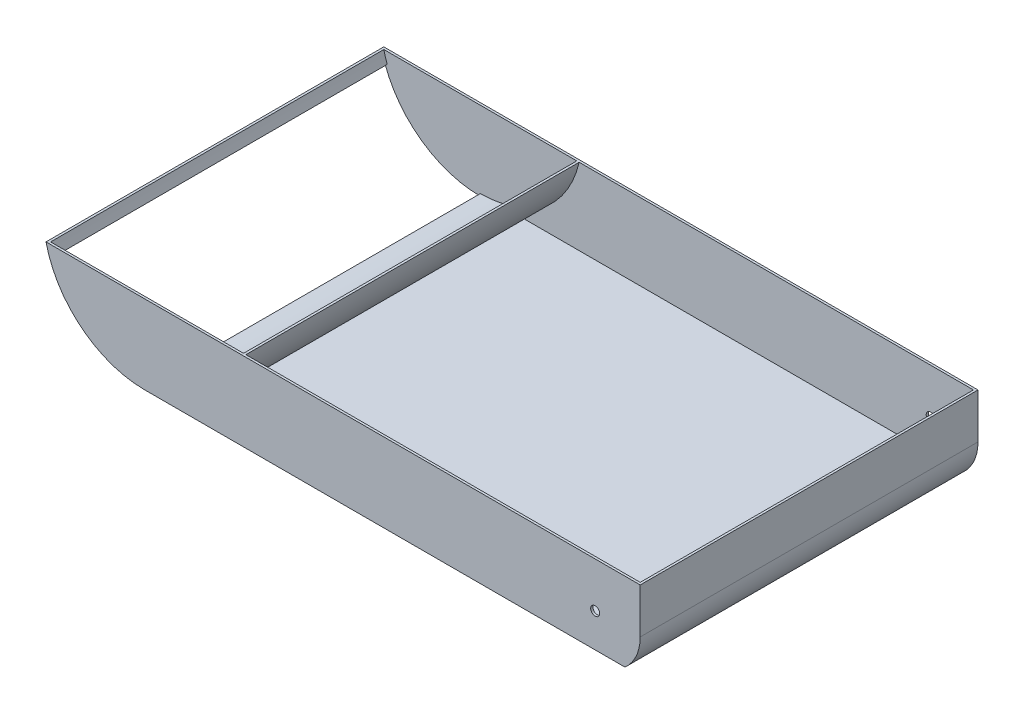
SolidWorks part; units mm, degrees
ref_plane "前视基准面" through (0, 0, 0) normal (0, 0, 1) x (1, 0, 0)
ref_plane "上视基准面" through (0, 0, 0) normal (0, 1, 0) x (1, 0, 0)
ref_plane "右视基准面" through (0, 0, 0) normal (1, 0, 0) x (0, 0, -1)
sketch "草图1" plane through (0, 0, 0) normal (0, 0, 1) x (1, 0, 0)
  line L6 (-22.8393, -20) -> (-87.7496, -20)
  line L7 (0, -90) -> (400, -90)
  line L8 (400, -90) -> (426.4575, -90)
  line L9 (-22.8393, -20) -> (400, -20)
  line L10 (440, -60) -> (440, -20)
  line L11 (440, -20) -> (400, -20)
  arc A0 (-87.7496, -20) -> (0, -90) centre (0, 0) ccw
  arc A5 (426.4575, -90) -> (440, -60) centre (400, -60) ccw
extrude "凸台-拉伸1" add sketch "草图1" against normal blind 300
shell "抽壳1" thickness 2
sketch "草图3" plane through (0, 0, -298) normal (0, 0, 1) x (1, 0, 0)
  line L0 (0, -90) -> (0, -30)
  line L1 (0, -30) -> (-101.2114, -30)
  line L2 (-101.2114, -30) -> (-101.2114, -90)
  line L3 (-101.2114, -90) -> (0, -90)
  dimension "D1" = 60
extrude "切除-拉伸1" cut sketch "草图3" along normal up to surface (296 mm away) up to face at (241.4168, -58.4456, -2)
sketch "草图4" plane through (0, 0, 0) normal (0, 0, 1) x (1, 0, 0)
  line L0 (85.6971, -20) -> (87.7496, -20)
  line L2 (0, -88) -> (0, -90)
  arc A0 (0, -90) -> (87.7496, -20) centre (0, 0) ccw
  arc A1 (0, -88) -> (85.6971, -20) centre (0, 0) ccw
extrude "凸台-拉伸2" add sketch "草图4" against normal up to surface (300 mm away) up to face at (241.9373, -59.3627, -300)
sketch "草图6" plane through (0, 0, 0) normal (0, 0, 1) x (1, 0, 0)
  circle A0 centre (400, -60) radius 4
extrude "切除-拉伸2" cut sketch "草图6" against normal through all both
